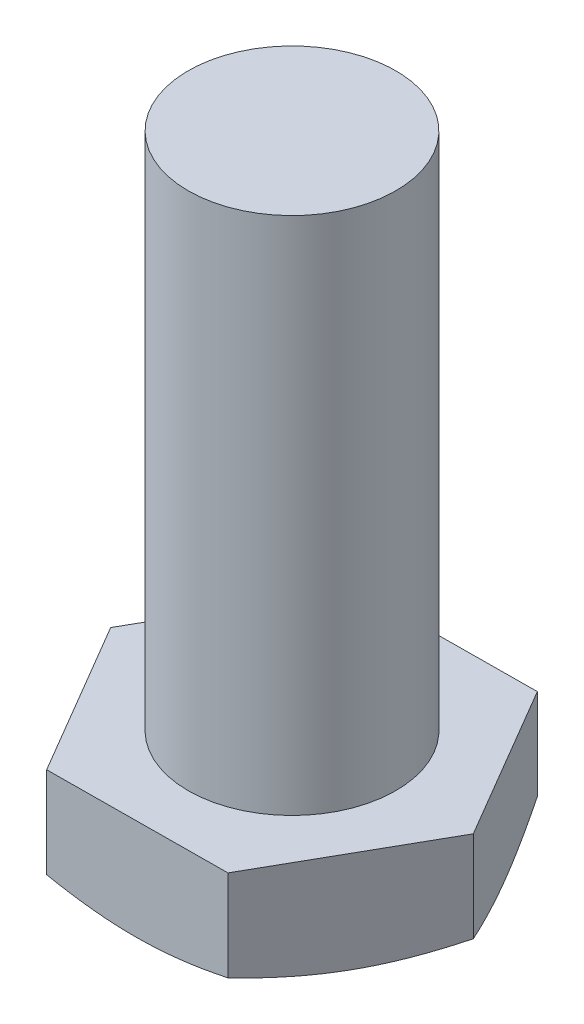
SolidWorks part; units mm, degrees
ref_plane "前视基准面" through (0, 0, 0) normal (0, 0, 1) x (1, 0, 0)
ref_plane "上视基准面" through (0, 0, 0) normal (0, 1, 0) x (1, 0, 0)
ref_plane "右视基准面" through (0, 0, 0) normal (1, 0, 0) x (0, 0, -1)
sketch "草图1" plane through (0, 0, 0) normal (0, 1, 0) x (1, 0, 0)
  line L1 (3.4191, 6.0258) -> (-3.5089, 5.9739)
  line L2 (-3.5089, 5.9739) -> (-6.928, -0.0518)
  line L3 (-6.928, -0.0518) -> (-3.4191, -6.0258)
  line L4 (-3.4191, -6.0258) -> (3.5089, -5.9739)
  line L5 (3.5089, -5.9739) -> (6.928, 0.0518)
  line L6 (6.928, 0.0518) -> (3.4191, 6.0258)
  circle A0 centre (0, 0) radius 6 construction
  dimension "D1" = 12
extrude "凸台-拉伸1" add sketch "草图1" along normal blind 4
sketch "草图2" plane through (0, 4, 0) normal (0, 1, 0) x (1, 0, 0)
  circle A0 centre (0, 0) radius 4
  dimension "D1" = 8
extrude "凸台-拉伸2" add sketch "草图2" along normal blind 20
ref_plane "基准面1" through (0, 0, 0) normal (0.8697, 0, 0.4935) x (0.4935, 0, -0.8697)
sketch "草图5" plane through (0, 0, 0) normal (0.8697, 0, 0.4935) x (0.4935, 0, -0.8697)
  line L0 (6.9282, 0.5) -> (5.7282, 0)
  line L1 (6.9282, 4) -> (6.9282, 0) construction
  line L2 (3.4641, 0) -> (6.9282, 0) construction
  line L3 (5.7282, 0) -> (6.9282, 0)
  line L4 (6.9282, 0) -> (6.9282, 0.5)
  line L5 (0, -1000) -> (0, 49000) construction
  dimension "D1" = 0.5
  dimension "D2" = 1.2
revolve "切除-旋转3" cut sketch "草图5" angle 360 about L5
